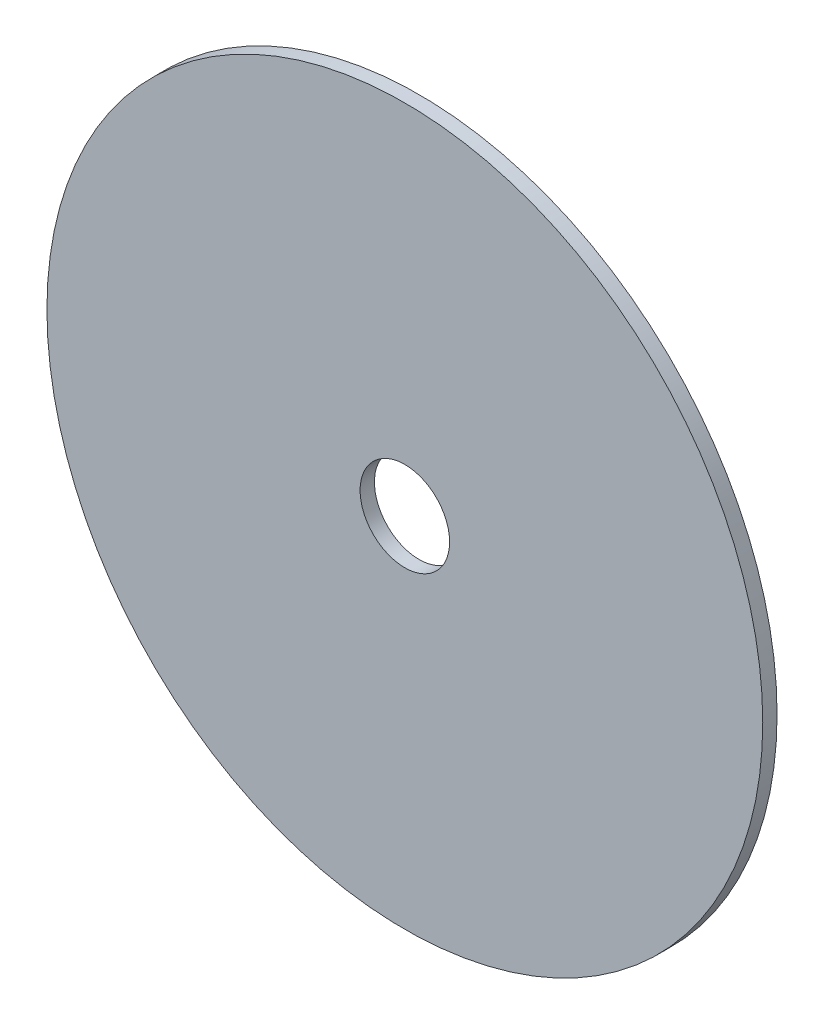
SolidWorks part; units mm, degrees
ref_plane "Plan de face" through (0, 0, 0) normal (0, 0, 1) x (1, 0, 0)
ref_plane "Plan de dessus" through (0, 0, 0) normal (0, 1, 0) x (1, 0, 0)
ref_plane "Plan de droite" through (0, 0, 0) normal (1, 0, 0) x (0, 0, -1)
sketch "Esquisse1" plane through (0, 0, 0) normal (0, 0, 1) x (1, 0, 0)
  circle A0 centre (0, 0) radius 40
  circle A1 centre (0, 0) radius 5
  dimension "D1" = 80
  dimension "D2" = 10
extrude "Boss.-Extru.1" add sketch "Esquisse1" along normal blind 1.6
